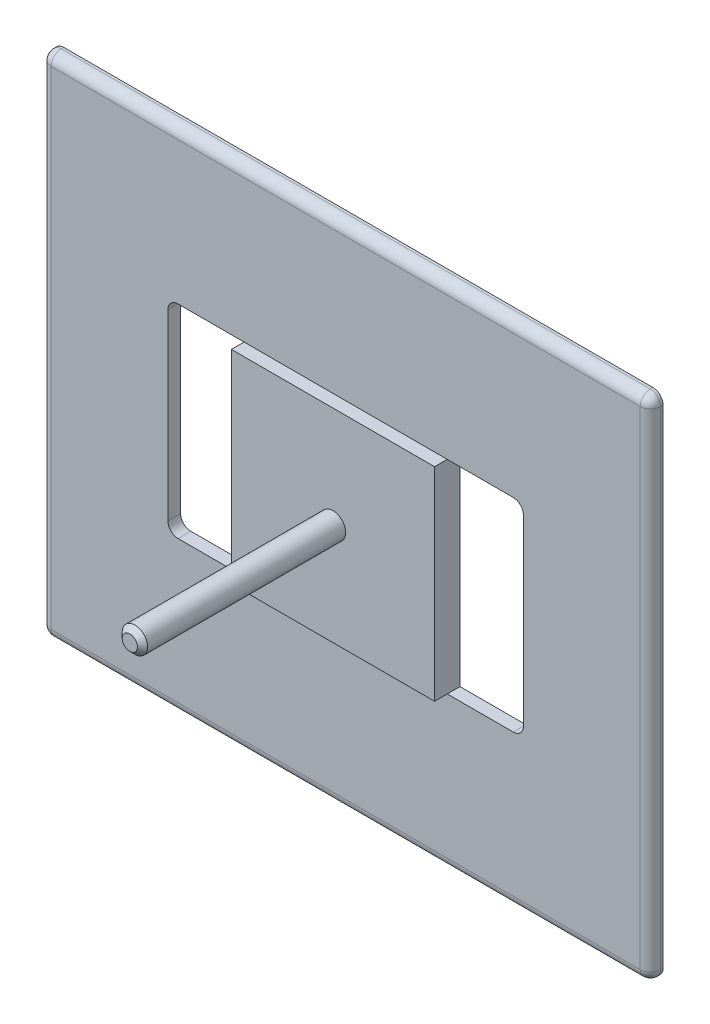
SolidWorks part; units mm, degrees
ref_plane "Front Plane" through (0, 0, 0) normal (0, 0, 1) x (1, 0, 0)
ref_plane "Top Plane" through (0, 0, 0) normal (0, 1, 0) x (1, 0, 0)
ref_plane "Right Plane" through (0, 0, 0) normal (1, 0, 0) x (0, 0, -1)
sketch "Sketch1" plane through (0, 0, 0) normal (0, 0, 1) x (1, 0, 0)
  line L1 (-60, -50) -> (60, -50)
  line L2 (-60, -50) -> (-60, 50)
  line L3 (-60, 50) -> (60, 50)
  line L4 (60, -50) -> (60, 50)
  line L5 (-60, -50) -> (60, 50) construction
  line L6 (-60, 50) -> (60, -50) construction
  circle A0 centre (0, 0) radius 2.5
  dimension "D1" = 5
  dimension "D2" = 100
  dimension "D3" = 120
extrude "Boss-Extrude1" add sketch "Sketch1" along normal blind 5
sketch "Sketch2" plane through (0, 0, 0) normal (0, 0, 1) x (1, 0, 0)
  circle A0 centre (0, 0) radius 2.5 construction
  circle A1 centre (0, 0) radius 2.5
extrude "Boss-Extrude2" add sketch "Sketch2" along normal blind 45
chamfer "Chamfer1" distance 1 angle 45 1 edges at (2.5, 0, 45)
sketch "Sketch3" plane through (0, 0, 5) normal (0, 0, 1) x (1, 0, 0)
  line L1 (-20, -20) -> (20, -20)
  line L2 (-20, -20) -> (-20, 20)
  line L3 (-20, 20) -> (20, 20)
  line L4 (20, -20) -> (20, 20)
  line L5 (-20, -20) -> (20, 20) construction
  line L6 (-20, 20) -> (20, -20) construction
  line L7 (-60, -50) -> (60, -50)
  line L8 (-60, -50) -> (-60, 50)
  line L9 (-60, 50) -> (60, 50)
  line L10 (60, -50) -> (60, 50)
  line L11 (-60, -50) -> (60, 50) construction
  line L12 (-60, 50) -> (60, -50) construction
  point P0 (0, 0)
  point P5 (0, 0)
  dimension "D1" = 40
extrude "Cut-Extrude1" cut sketch "Sketch3" against normal blind 2.5
sketch "Sketch6" plane through (0, 0, 2.5) normal (0, 0, 1) x (1, 0, 0)
  line L1 (-20, 20) -> (-35, 20)
  line L2 (-20, 20) -> (-20, -20)
  line L3 (-20, -20) -> (-35, -20)
  line L4 (-35, 20) -> (-35, -20)
  line L5 (20, 20) -> (35, 20)
  line L6 (20, 20) -> (20, -20)
  line L7 (20, -20) -> (35, -20)
  line L8 (35, 20) -> (35, -20)
  dimension "D1" = 40
  dimension "D2" = 15
  dimension "D3" = 40
  dimension "D4" = 15
extrude "Cut-Extrude2" cut sketch "Sketch6" against normal through all
fillet "Fillet1" radius 2 8 edges at (-60, 50, 1.25) (60, 50, 1.25) (60, -50, 1.25) (-60, -50, 1.25) (0, -50, 2.5) (-60, 0, 2.5) (0, 50, 2.5) (60, 0, 2.5)
fillet "Fillet2" radius 2 4 edges at (-35, -20, 1.25) (35, -20, 1.25) (-35, 20, 1.25) (35, 20, 1.25)
